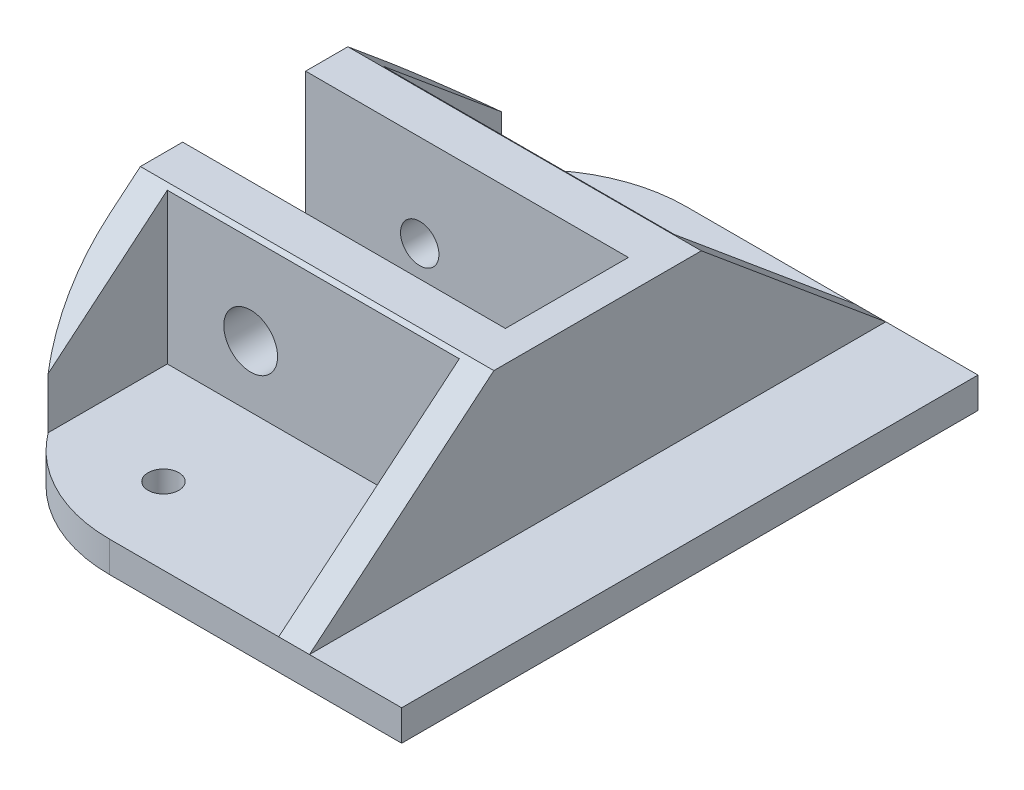
SolidWorks part; units mm, degrees
ref_plane "Front Plane" through (0, 0, 0) normal (0, 0, 1) x (1, 0, 0)
ref_plane "Top Plane" through (0, 0, 0) normal (0, 1, 0) x (1, 0, 0)
ref_plane "Right Plane" through (0, 0, 0) normal (1, 0, 0) x (0, 0, -1)
sketch "TopSketch1" plane through (0, 0, 0) normal (0, 1, 0) x (1, 0, 0)
  line L0 (0, 0) -> (29, 0)
  line L1 (29, 0) -> (29, 37.5)
  line L2 (29, 37.5) -> (0, 37.5)
  line L3 (0, 37.5) -> (0, 22.75)
  line L4 (0, 22.75) -> (21, 22.75)
  line L5 (21, 22.75) -> (21, 14.75)
  line L6 (21, 14.75) -> (0, 14.75)
  line L7 (0, 14.75) -> (0, 0)
  circle A0 centre (8.5, 32.5) radius 1
  circle A1 centre (8.5, 5) radius 1
  dimension "D6" = 2
  dimension "D1" = 37.5
  dimension "D2" = 29
  dimension "D3" = 21
  dimension "D4" = 8
  dimension "D5" = 8.5
  dimension "D7" = 5
  dimension "D8" = 5
extrude "TopBoss-Extrude1" add sketch "TopSketch1" along normal blind 2
sketch "RailClampSketch2" plane through (0, 2, 0) normal (0, 1, 0) x (1, 0, 0)
  line L0 (0, 37.5) -> (0, 22.75)
  line L1 (0, 22.75) -> (21, 22.75)
  line L2 (21, 22.75) -> (21, 14.75)
  line L3 (21, 14.75) -> (0, 14.75)
  line L4 (0, 14.75) -> (0, 0)
  line L5 (0, 0) -> (2, 0)
  line L6 (2, 0) -> (2, 11.75)
  line L7 (2, 11.75) -> (21, 11.75)
  line L8 (21, 11.75) -> (21, 0)
  line L9 (21, 0) -> (23, 0)
  line L10 (23, 0) -> (23, 37.5)
  line L11 (23, 37.5) -> (21, 37.5)
  line L12 (21, 37.5) -> (21, 25.75)
  line L13 (21, 25.75) -> (2, 25.75)
  line L14 (2, 25.75) -> (2, 37.5)
  line L15 (2, 37.5) -> (0, 37.5)
  line L16 (29, 37.5) -> (0, 37.5) construction
  line L17 (0, 0) -> (29, 0) construction
  line L18 (29, 0) -> (29, 37.5) construction
  line L19 (0, 22.75) -> (21, 22.75) construction
  line L20 (21, 14.75) -> (0, 14.75) construction
  line L22 (0, 14.75) -> (0, 0) construction
  line L23 (0, 37.5) -> (0, 22.75) construction
  line L25 (21, 22.75) -> (21, 14.75) construction
  line L26 (0, 37.5) -> (0, 22.75) construction
  line L27 (0, 22.75) -> (21, 22.75) construction
  dimension "D1" = 2
  dimension "D2" = 3
extrude "RailClampBoss-Extrude2" add sketch "RailClampSketch2" along normal blind 10
sketch "RailScrewSide1HoleSketch3" plane through (0, 0, -11.75) normal (0, 0, 1) x (1, 0, 0)
  line L1 (2, 12) -> (21, 12) construction
  line L3 (0, 12) -> (0, 0) construction
  circle A0 centre (7.425, 6) radius 1.75
  dimension "D3" = 3.5
  dimension "D2" = 6
  dimension "D1" = 7.425
extrude "RailScrewSide1HoleCut-Extrude1" cut sketch "RailScrewSide1HoleSketch3" against normal up to next
sketch "RailScrewSide2HoleSketch4" plane through (0, 0, -25.75) normal (0, 0, -1) x (-1, 0, 0)
  circle A0 centre (-7.425, 6) radius 1.25
  circle A1 centre (-7.425, 6) radius 1.75 construction
  dimension "D1" = 2.5
extrude "RailScrewSide2HoleCut-Extrude2" cut sketch "RailScrewSide2HoleSketch4" against normal up to next
fillet "Fillet1" radius 10 2 edges at (0, 6, 0) (0, 6, -37.5)
chamfer "Chamfer2" distance 10 distance2 12 2 edges at (22, 12, -37.5) (22, 12, 0)
equation "\"GABDepth\"= \"GABDistanceFromBackToFirstPulley\" + \"GABPulleyDDistanceBetween\" + \"GABDistanceFromPulleyToFront\""
equation "\"GABWidth\"= \"StandardWallThickness\" + \"GABDistanceFromLSideToPulley\" + \"GABPulleyWDistanceBetween\" + \"GABDistanceFromPulleyToRSide\""
equation "\"StandardWallThickness\"= 3mm"
equation "\"LinearRailWidth\"= 12mm'Spec"
equation "\"LinearRailHeight\"= 8mm'Spec"
equation "\"GABLRClampHoleOffsetFromSide\"= 5mm"
equation "\"GABDistanceFromBackToFirstPulley\"= 13.5mm"
equation "\"GABPulleyDDistanceBetween\"= 12.5mm'From the100"
equation "\"GABPulleyWDistanceBetween\"= 14.5mm'From the100"
equation "\"GABDistanceFromPulleyToFront\"= 8mm"
equation "\"GABDistanceFromLSideToPulley\"= 9.5mm + \"StandardWallThickness\""
equation "\"GABDistanceFromPulleyToRSide\"= 7.5mm"
equation "\"GABClampBaseHeight\"= 2mm"
equation "\"LinearRailHoleDiameter\"= 3.5mm'Spec"
equation "\"GABDistanceToFrontClampHoles\"= 8.5mm"
equation "\"GABClampLinearRailFasteningHoleDiameter\"= \"LinearRailHoleDiameter\" - 1mm"
equation "\"LinearRailFirstHoleOffsetFromEdge\"= 12.5mm'Spec"
equation "\"GABClampDepth\"= \"GABDepth\" - 5mm"
equation "\"GABClampLinearRailDepth\"= \"GABClampDepth\" - 8mm"
equation "\"D1@TopSketch1\" = \"GABWidth\""
equation "\"D2@TopSketch1\" = \"GABClampDepth\""
equation "\"D3@TopSketch1\" = \"GABClampLinearRailDepth\""
equation "\"D4@TopSketch1\" = \"LinearRailHeight\""
equation "\"D5@TopSketch1\" = \"GABDistanceToFrontClampHoles\""
equation "\"D7@TopSketch1\" = \"GABLRClampHoleOffsetFromSide\""
equation "\"D8@TopSketch1\" = \"GABLRClampHoleOffsetFromSide\""
equation "\"D1@TopBoss-Extrude1\" = \"GABClampBaseHeight\""
equation "\"D2@RailClampSketch2\" = \"StandardWallThickness\""
equation "\"D1@RailClampBoss-Extrude2\" = \"LinearRailWidth\" - \"GABClampBaseHeight\""
equation "\"D2@RailScrewSide1HoleSketch3\" = \"LinearRailWidth\" / 2"
equation "\"D3@RailScrewSide1HoleSketch3\" = \"LinearRailHoleDiameter\""
equation "\"D1@RailScrewSide2HoleSketch4\" = \"GABClampLinearRailFasteningHoleDiameter\""
equation "\"GABDistanceFromBackToClampFront\"= \"GABDistanceFromBackToFirstPulley\" + \"GABPulleyDDistanceBetween\" + \"GABDistanceFromPulleyToFront\""
equation "\"DistanceBetweenFrontOfLinearRailClamps\"= \"FrontBackRailLength\" - \"RailThickness\" * 2 - \"LinearGBWithRailDepth\" * 2 - \"GABDistanceFromBackToClampFront\" * 2"
equation "\"FrontBackRailLength\"= 510mm"
equation "\"RailThickness\"= .125in'Spec"
equation "\"LinearRailLength\"= 450mm'Spec"
equation "\"LinearGBWithRailDepth\"= 12.75mm'Spec"
equation "\"GABClampFrontToLinearRailMountingHole\"= ( \"LinearRailLength\" - \"DistanceBetweenFrontOfLinearRailClamps\" - \"LinearRailFirstHoleOffsetFromEdge\" * 2 ) / 2"
equation "\"D1@RailScrewSide1HoleSketch3\"=\"GABClampFrontToLinearRailMountingHole\""
